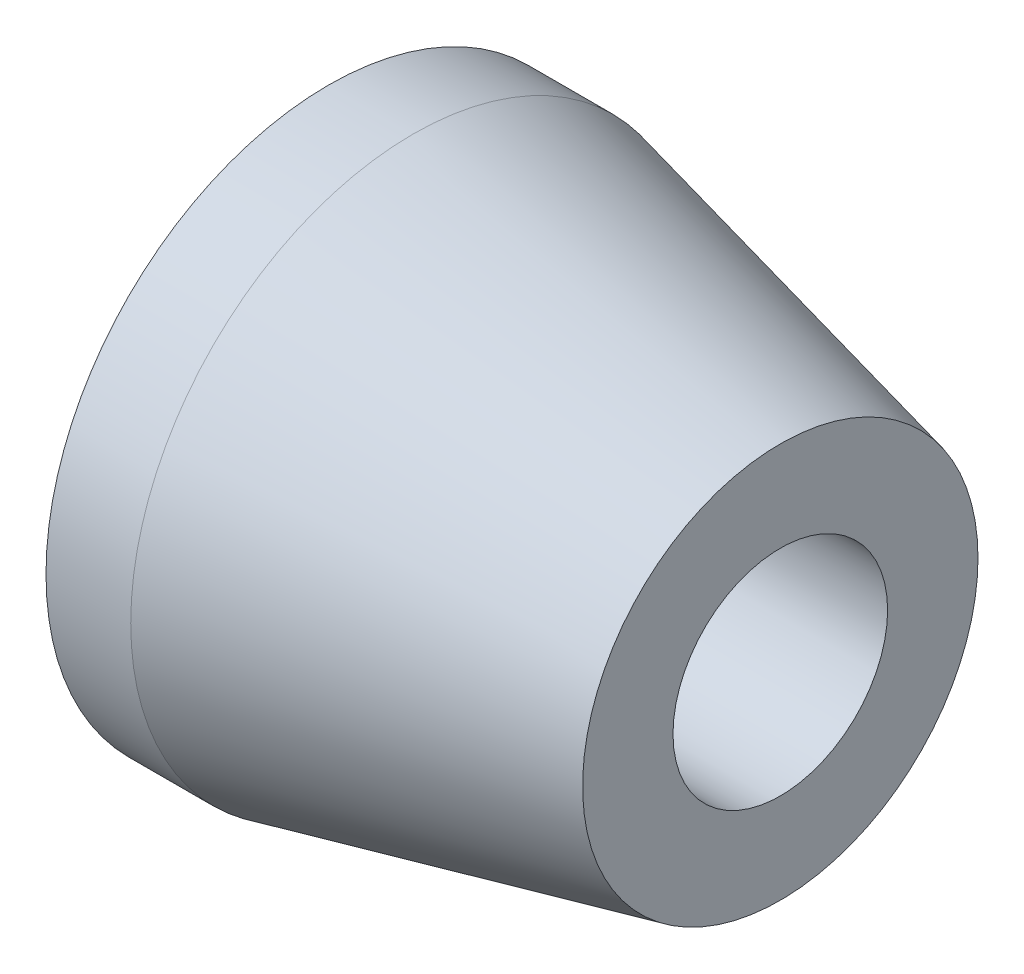
SolidWorks part; units mm, degrees
material "Gray Cast Iron (SN)"
ref_plane "Front Plane" through (0, 0, 0) normal (0, 0, 1) x (1, 0, 0)
ref_plane "Top Plane" through (0, 0, 0) normal (0, 1, 0) x (1, 0, 0)
ref_plane "Right Plane" through (0, 0, 0) normal (1, 0, 0) x (0, 0, -1)
sketch "Sketch1" plane through (0, 0, 0) normal (0, 0, 1) x (1, 0, 0)
  line L0 (0, 3.8) -> (0, 0) construction
  line L1 (0, 0) -> (-22.4526, 0) construction
  line L2 (0, 3.8) -> (-14, 3.8)
  line L3 (-14, 3.8) -> (-14, 5.5)
  line L4 (-14, 5.5) -> (-16, 5.5)
  line L5 (-16, 5.5) -> (-16, 10)
  line L6 (-16, 10) -> (-13, 10)
  line L7 (-13, 10) -> (0, 7)
  line L8 (0, 7) -> (0, 3.8)
  point P9 (-23.618, -2.1566)
  point P11 (-18.3881, -2.1566)
  point P12 (-19.4422, 2.0428)
  point P13 (-18.1448, 5.2862)
  dimension "D1" = 7.6
  dimension "D2" = 14
  dimension "D3" = 20
  dimension "D4" = 11
  dimension "D5" = 2
  dimension "D6" = 3
  dimension "D7" = 16
revolve "Revolve1" add sketch "Sketch1" angle 360 about L1
